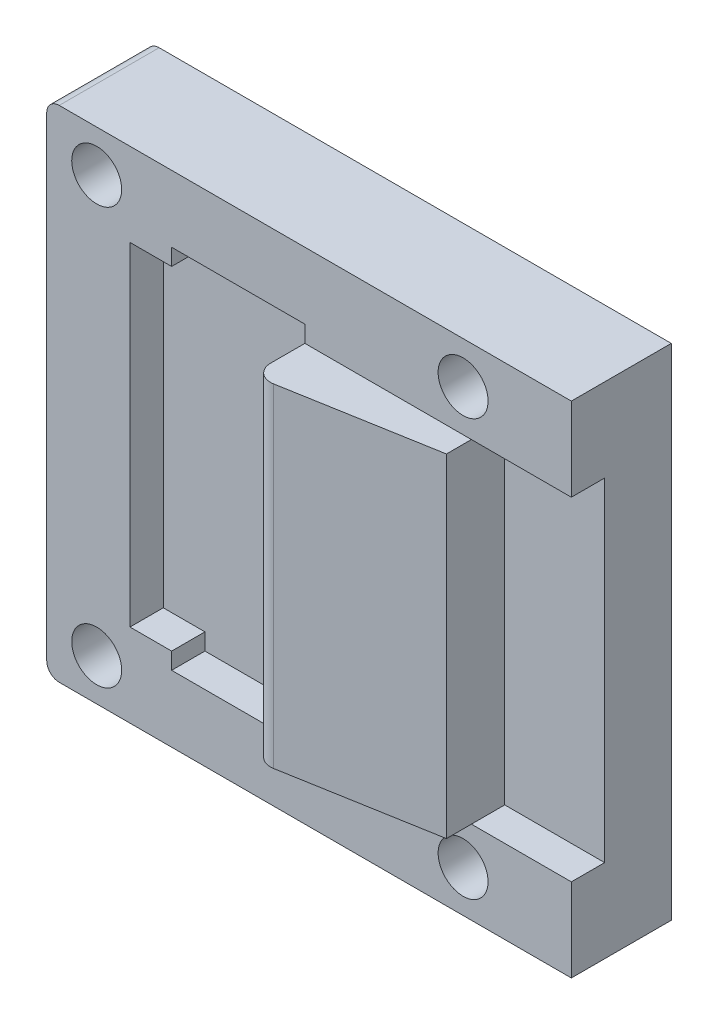
SolidWorks part; units mm, degrees
ref_plane "Ebene vorne" through (0, 0, 0) normal (0, 0, 1) x (1, 0, 0)
ref_plane "Ebene oben" through (0, 0, 0) normal (0, 1, 0) x (1, 0, 0)
ref_plane "Ebene rechts" through (0, 0, 0) normal (1, 0, 0) x (0, 0, -1)
sketch "Sketch1" plane through (0, 0, 0) normal (0, 0, 1) x (1, 0, 0)
  line L1 (15, -10) -> (-15, -10)
  line L2 (15, -10) -> (15, 10)
  line L3 (15, 10) -> (-15, 10)
  line L4 (-15, -10) -> (-15, 10)
  line L5 (15, -10) -> (-15, 10) construction
  line L6 (15, 10) -> (-15, -10) construction
  point P0 (0, 0)
  dimension "D1" = 20
  dimension "D2" = 30
extrude "Base Plate" add sketch "Sketch1" along normal blind 1
sketch "Sketch2" plane through (0, 0, 0) normal (0, 0, -1) x (1, 0, 0)
  line L1 (15, 10) -> (-15, 10)
  line L2 (15, 10) -> (15, 15)
  line L3 (15, 15) -> (-20, 15)
  line L5 (15, -10) -> (-15, -10)
  line L6 (15, -10) -> (15, -15)
  line L7 (15, -15) -> (-20, -15)
  line L11 (-15, -10) -> (-15, 10)
  line L13 (-20, -15) -> (-20, 15)
  dimension "D1" = 5
  dimension "D2" = 5
  dimension "D3" = 5
extrude "Side Walls" add sketch "Sketch2" against normal blind 6
sketch "Sketch3" plane through (0, 0, 1) normal (0, 0, 1) x (1, 0, 0)
  line L0 (15, 10) -> (-15, 10) construction
  line L1 (5.5, -10) -> (-4.5, -10)
  line L2 (5.5, -10) -> (5.5, 10)
  line L3 (5.5, 10) -> (-4.5, 10)
  line L4 (-4.5, -10) -> (-4.5, 10)
  line L5 (15, -10) -> (15, 10) construction
  line L6 (-15, -10) -> (15, -10) construction
  dimension "D1" = 10
  dimension "D2" = 9.5
extrude "Switch Block" add sketch "Sketch3" along direction (0, 0, -1) on the side of the normal offset from surface (6.5 mm away) 1.5
sketch "Sketch11" plane through (0, 0, 1) normal (0, 0, 1) x (1, 0, 0)
  line L1 (-15, -10) -> (-4.5, -10)
  line L2 (-15, -10) -> (-15, 10)
  line L3 (-15, 10) -> (-4.5, 10)
  line L4 (-4.5, -10) -> (-4.5, 10)
  line L5 (5.5, 10) -> (15, 10)
  line L6 (5.5, 10) -> (5.5, -10)
  line L7 (5.5, -10) -> (15, -10)
  line L8 (15, 10) -> (15, -10)
extrude "Thicker Body" add sketch "Sketch11" along normal offset from surface (3 mm away) 4 up to face at (-2.5, 0, 0)
sketch "Sketch5" plane through (0, 10, 0) normal (0, 1, 0) x (-1, 0, 0)
  line L0 (4.5, 7.5) -> (4.5, 9.25)
  line L1 (4.5, 9.25) -> (-5.5, 7.5)
  line L2 (-5.5, 7.5) -> (4.5, 7.5)
  dimension "D1" = 1.75
extrude "Switch Block Angle" add sketch "Sketch5" against normal up to surface (20 mm away) up to face at (0.5, -10, 6.75)
sketch "Sketch4" plane through (0, 0, 6) normal (0, 0, 1) x (1, 0, 0)
  line L0 (-20, -15) -> (-20, 15) construction
  line L2 (15, -10) -> (15, -15) construction
  line L3 (-15, 0) -> (-8.5625, 0) construction
  line L4 (-15, 10) -> (-15, -10) construction
  line L5 (15, -12.5) -> (1.31, -12.5) construction
  circle A0 centre (-17, -12.5) radius 1.5
  circle A1 centre (5, -12.5) radius 1.5
  circle A2 centre (5, 12.5) radius 1.5
  circle A3 centre (-17, 12.5) radius 1.5
  dimension "D1" = 3
  dimension "D2" = 3
  dimension "D5" = 10
extrude "M2 Screws" cut sketch "Sketch4" against normal up to surface (6 mm away) up to face at (-2.5, 0, 0)
fillet "Fillet1" radius 1 1 edges at (-4.5, 0, 9.25)
fillet "Fillet2" radius 0.5 1 edges at (15, -15, 3)
fillet "Fillet3" radius 0.5 1 edges at (15, 15, 3)
fillet "Fillet4" radius 0.75 1 edges at (-20, 15, 3)
fillet "Fillet5" radius 0.75 1 edges at (-20, -15, 3)
sketch "Sketch19" plane through (0, 0, 6) normal (0, 0, 1) x (1, 0, 0)
  line L0 (-15, -10) -> (-4.5, -10) construction
  line L1 (-12.5, 11) -> (-4.5, 11)
  line L2 (-12.5, 11) -> (-12.5, -11)
  line L3 (-12.5, -11) -> (-4.5, -11)
  line L4 (-4.5, 11) -> (-4.5, -11)
  line L5 (-4.5, 10) -> (-15, 10) construction
  dimension "D1" = 1
  dimension "D2" = 1
  dimension "D3" = 8
extrude "Space for LEaver" cut sketch "Sketch19" against normal up to surface (2 mm away) up to face at (-9.75, 0, 4)
sketch "Sketch20" plane through (0, 0, 0) normal (0, 0, -1) x (1, 0, 0)
  line L0 (5, 12.5) -> (5, -12.5) construction
  line L1 (7.5, 0) -> (6.3537, 0) construction
  line L2 (7.5, 2.5) -> (-20, 2.5)
  line L3 (7.5, 2.5) -> (7.5, -2.5)
  line L4 (7.5, -2.5) -> (-20, -2.5)
  line L5 (-20, 2.5) -> (-20, -2.5)
  line L6 (5, 0) -> (2.1521, 0) construction
  line L7 (-20, 14.25) -> (-20, -14.25) construction
  dimension "D1" = 2.5
  dimension "D2" = 5
extrude "Cut-Extrude1" cut sketch "Sketch20" against normal blind 2
sketch "Sketch21" plane through (0, 0, 4) normal (0, 0, 1) x (1, 0, 0)
  line L0 (15, -10) -> (15, 10) construction
  line L1 (11.5, 18.8407) -> (32.2821, 18.8407)
  line L2 (11.5, 18.8407) -> (11.5, -22.787)
  line L3 (11.5, -22.787) -> (32.2821, -22.787)
  line L4 (32.2821, 18.8407) -> (32.2821, -22.787)
  dimension "D1" = 3.5
extrude "Cut-Extrude2" cut sketch "Sketch21" against normal through all both and the other way through all
